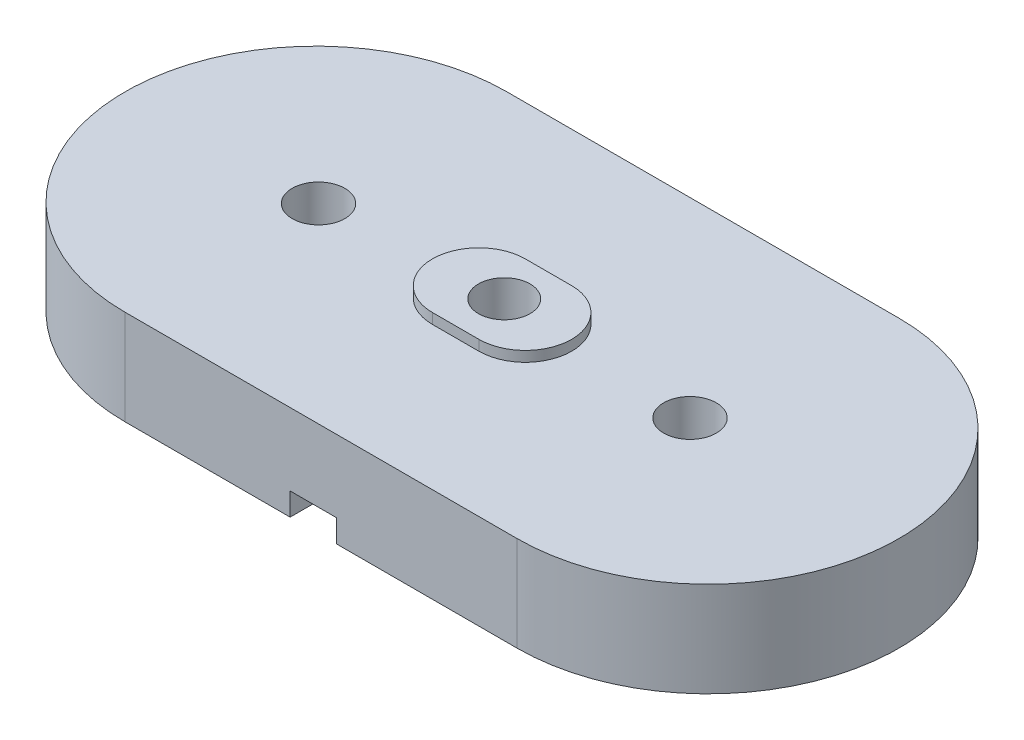
SolidWorks part; units mm, degrees
ref_plane "Front Plane" through (0, 0, 0) normal (0, 0, 1) x (1, 0, 0)
ref_plane "Top Plane" through (0, 0, 0) normal (0, 1, 0) x (1, 0, 0)
ref_plane "Right Plane" through (0, 0, 0) normal (1, 0, 0) x (0, 0, -1)
sketch "Sketch1" plane through (0, 0, 0) normal (0, 1, 0) x (1, 0, 0)
  line L0 (0, 92.5) -> (190, 92.5)
  line L1 (0, -92.5) -> (190, -92.5)
  arc A0 (0, 92.5) -> (0, -92.5) centre (0, 0) ccw
  arc A1 (190, -92.5) -> (190, 92.5) centre (190, 0) ccw
  dimension "D1" = 185
  dimension "D2" = 190
extrude "Boss-Extrude1" add sketch "Sketch1" along normal blind 46
sketch "Sketch2" plane through (0, 0, 0) normal (0, -1, 0) x (1, 0, 0)
  line L0 (80, -92.5) -> (80, -22.5)
  line L1 (102.5, 0) -> (80, 0) construction
  line L2 (91.25, -907.5) -> (91.25, 49092.5) construction
  line L3 (0, 92.5) -> (190, 92.5) construction
  line L4 (80, 22.5) -> (80, 92.5)
  line L5 (102.5, -92.5) -> (102.5, -22.5)
  line L6 (102.5, 22.5) -> (102.5, 92.5)
  line L7 (80, 92.5) -> (102.5, 92.5)
  line L8 (80, -92.5) -> (102.5, -92.5)
  arc A0 (80, 22.5) -> (80, -22.5) centre (80, 0) ccw
  arc A1 (102.5, 22.5) -> (102.5, -22.5) centre (102.5, 0) cw
  point P5 (91.25, 0)
  point P6 (102.5, 0)
  point P13 (80, 0)
  dimension "D1" = 45
extrude "Cut-Extrude1" cut sketch "Sketch2" against normal blind 11
sketch "Sketch3" plane through (0, 11, 0) normal (0, -1, 0) x (1, 0, 0)
  line L0 (91.25, 1092.5) -> (91.25, 92.5) construction
  line L1 (91.25, 12.5) -> (91.25, -12.5) construction
  line L2 (91.25, -92.5) -> (91.25, -49907.5) construction
  line L6 (80, -92.5) -> (102.5, -92.5)
  line L7 (102.5, -92.5) -> (102.5, -22.5)
  line L8 (102.5, 22.5) -> (102.5, 92.5)
  line L9 (102.5, 92.5) -> (80, 92.5)
  line L10 (80, 92.5) -> (80, 22.5)
  line L11 (80, -22.5) -> (80, -92.5)
  line L12 (80, -92.5) -> (102.5, -92.5)
  line L15 (102.5, 92.5) -> (80, 92.5)
  circle A0 centre (91.25, 0) radius 12.5
  arc A2 (102.5, -22.5) -> (102.5, 22.5) centre (102.5, 0) ccw
  arc A3 (80, 22.5) -> (80, -22.5) centre (80, 0) ccw
  point P9 (91.25, 92.5)
  dimension "D2" = 25
  dimension "D1" = 0
extrude "Cut-Extrude2" cut sketch "Sketch3" against normal through all contours A0
sketch "Sketch4" plane through (0, 46, 0) normal (0, 1, 0) x (1, 0, 0)
  line L1 (102.0895, -0.6498) -> (79.5895, -0.6498) construction
  line L2 (90.8395, -908.1498) -> (90.8395, 49091.8502) construction
  line L6 (79.5895, 91.8502) -> (102.0895, 91.8502)
  line L7 (79.5895, -93.1498) -> (102.0895, -93.1498)
  line L8 (79.5895, 21.8502) -> (102.0895, 21.8502)
  line L9 (79.5895, -23.1498) -> (102.0895, -23.1498)
  arc A0 (79.5895, 21.8502) -> (79.5895, -23.1498) centre (79.5895, -0.6498) ccw
  arc A1 (102.0895, 21.8502) -> (102.0895, -23.1498) centre (102.0895, -0.6498) cw
  circle A2 centre (91.25, 0) radius 12.5 construction
  circle A3 centre (91.25, 0) radius 12.5
  point P5 (90.8395, -0.6498)
  point P6 (102.0895, -0.6498)
  point P11 (79.5895, -0.6498)
  circle M12 centre (91.25, 0) radius 12.5
extrude "Boss-Extrude2" add sketch "Sketch4" along normal blind 5 contours A1 L8 A0 L9 M12
sketch "Sketch5" plane through (0, 46, 0) normal (0, 1, 0) x (1, 0, 0)
  line L0 (181.25, 0) -> (1.25, 0) construction
  circle A0 centre (1.25, 0) radius 12.75
  circle A1 centre (181.25, 0) radius 12.75
  point P4 (91.25, 0)
  dimension "D1" = 25.5
  dimension "D2" = 180
extrude "Cut-Extrude3" cut sketch "Sketch5" against normal through all both and the other way through all
